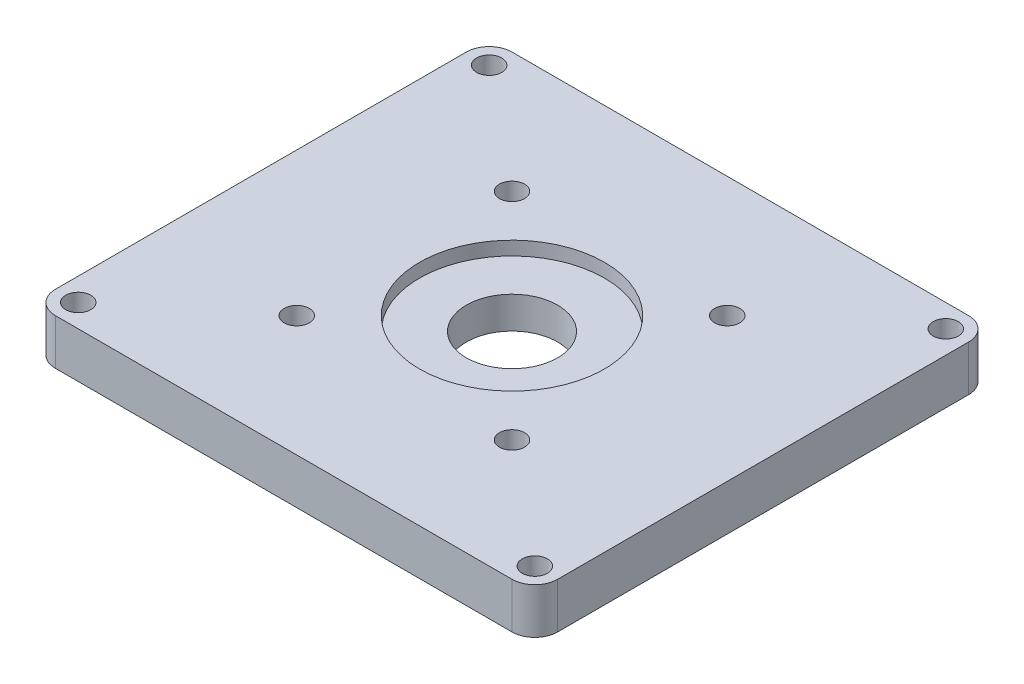
SolidWorks part; units mm, degrees
ref_plane "Front Plane" through (0, 0, 0) normal (0, 0, 1) x (1, 0, 0)
ref_plane "Top Plane" through (0, 0, 0) normal (0, 1, 0) x (1, 0, 0)
ref_plane "Right Plane" through (0, 0, 0) normal (1, 0, 0) x (0, 0, -1)
sketch "Sketch2" plane through (0, 0, 0) normal (0, 1, 0) x (1, 0, 0)
  line L1 (0, 0) -> (47.14, 0)
  line L2 (0, 0) -> (0, 47.14)
  line L3 (0, 47.14) -> (47.14, 47.14)
  line L4 (47.14, 0) -> (47.14, 47.14)
  line L5 (-26.43, 68.57) -> (73.57, 68.57)
  line L6 (-26.43, 68.57) -> (-26.43, -21.43)
  line L7 (-26.43, -21.43) -> (73.57, -21.43)
  line L8 (73.57, 68.57) -> (73.57, -21.43)
  line L9 (-31.43, 73.57) -> (78.57, 73.57)
  line L10 (-31.43, 73.57) -> (-31.43, -26.43)
  line L11 (-31.43, -26.43) -> (78.57, -26.43)
  line L12 (78.57, 73.57) -> (78.57, -26.43)
  circle A0 centre (0, 47.14) radius 2.75
  circle A1 centre (47.14, 47.14) radius 2.75
  circle A2 centre (47.14, 0) radius 2.75
  circle A3 centre (0, 0) radius 2.75
  circle A4 centre (-26.43, 68.57) radius 2.75
  circle A5 centre (73.57, 68.57) radius 2.75
  circle A6 centre (73.57, -21.43) radius 2.75
  circle A7 centre (-26.43, -21.43) radius 2.75
  dimension "D3" = 100
  dimension "D7" = 110
  dimension "D1" = 47.14
  dimension "D2" = 47.14
  dimension "D4" = 90
  dimension "D5" = 21.43
  dimension "D6" = 26.43
  dimension "D8" = 100
  dimension "D9" = 5
  dimension "D10" = 5
extrude "Boss-Extrude1" add sketch "Sketch2" along normal blind 10 contours L12 L9 L10 L11 A7 L6 A4 L5 A5 L8 A6 L7 | A7 L7 A6 L8 A5 L5 A4 L6 A3 L2 A0 L3 A1 L4 A2 L1 | A3 L1 A2 L4 A1 L3 A0 L2
sketch "Sketch3" plane through (0, 10, 0) normal (0, 1, 0) x (1, 0, 0)
  circle A0 centre (23.57, 23.57) radius 10
extrude "Cut-Extrude1" cut sketch "Sketch3" against normal blind 10
sketch "Sketch4" plane through (0, 10, 0) normal (0, 1, 0) x (1, 0, 0)
  circle A0 centre (23.57, 23.57) radius 20.25
extrude "Cut-Extrude2" cut sketch "Sketch4" against normal blind 3
sketch "Sketch5" plane through (0, 0, 0) normal (0, -1, 0) x (1, 0, 0)
  circle A0 centre (0, 0) radius 6.25
  circle A1 centre (47.14, 0) radius 6.25
  circle A2 centre (47.14, -47.14) radius 6.25
  circle A3 centre (0, -47.14) radius 6.25
extrude "Cut-Extrude3" cut sketch "Sketch5" against normal blind 5.5
fillet "Fillet1" radius 5 4 edges at (-31.43, 5, -73.57) (78.57, 5, -73.57) (78.57, 5, 26.43) (-31.43, 5, 26.43)
